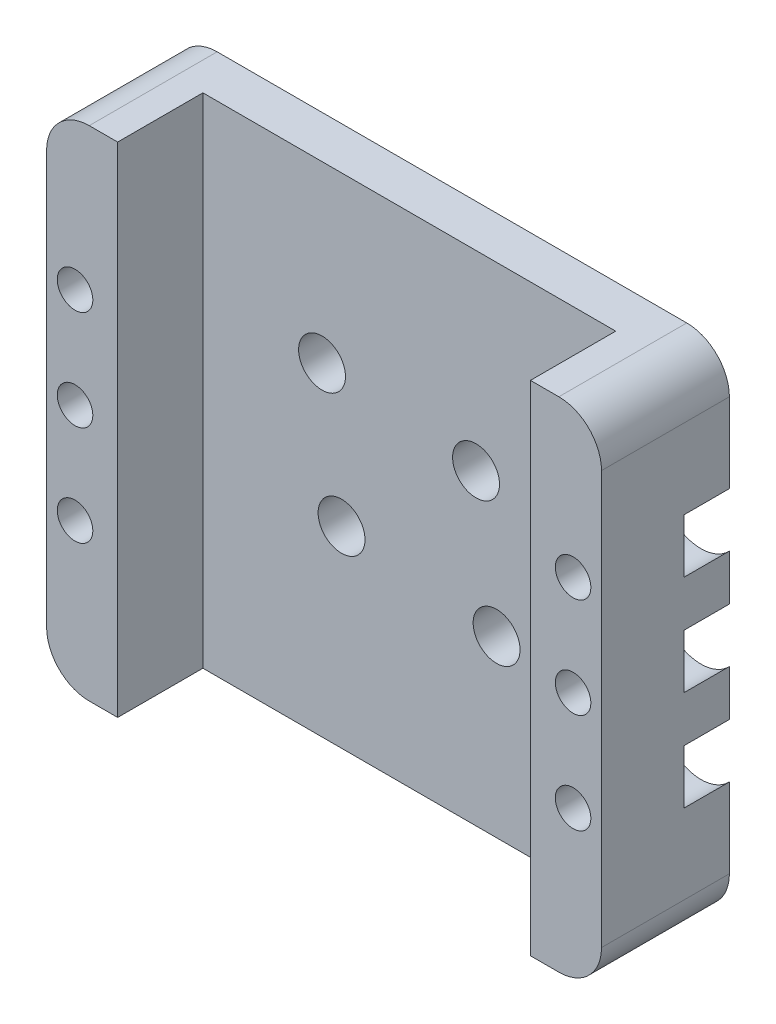
SolidWorks part; units mm, degrees
ref_plane "前视基准面" through (0, 0, 0) normal (0, 0, 1) x (1, 0, 0)
ref_plane "上视基准面" through (0, 0, 0) normal (0, 1, 0) x (1, 0, 0)
ref_plane "右视基准面" through (0, 0, 0) normal (1, 0, 0) x (0, 0, -1)
other "Configuration Table"
sketch "草图1" plane through (0, 0, 0) normal (0, 0, 1) x (-1, 0, 0)
  line L4 (-76.1943, 36.1142) -> (-76.1943, 1.0442)
  line L6 (-37.1443, 36.1142) -> (-37.1443, 1.0442)
  line L8 (-76.1943, 36.1142) -> (-37.1443, 36.1142)
  line L9 (-71.1943, 1.0442) -> (-71.1943, 36.1142)
  line L12 (-42.1443, 1.0442) -> (-42.1443, 36.1142)
  line L14 (-37.1443, 1.0442) -> (-76.1943, 1.0442)
  circle A6 centre (-62.8113, 23.8367) radius 1.65
  circle A9 centre (-50.5272, 13.3216) radius 1.65
  circle A11 centre (-74.1943, 25.6142) radius 1.25
  circle A12 centre (-74.1943, 11.5442) radius 1.25
  circle A13 centre (-74.1943, 18.5792) radius 1.25
  circle A14 centre (-39.1443, 25.6142) radius 1.25
  circle A15 centre (-39.1443, 18.5792) radius 1.25
  circle A16 centre (-39.1443, 11.5442) radius 1.25
  circle A17 centre (-51.9, 22.5808) radius 1.65
  circle A18 centre (-61.3649, 14.4695) radius 1.65
  point P3 (-74.1943, 36.1142)
  point P17 (-39.1443, 36.1142)
extrude "凸台-拉伸1" add sketch "草图1" along normal blind 3
sketch "草图2" plane through (0, 0, 0) normal (0, 0, -1) x (-1, 0, 0)
  line L0 (-76.1943, -1.0442) -> (-71.1943, -1.0442)
  line L1 (-37.1443, -1.0442) -> (-76.1943, -1.0442) construction
  line L2 (-71.1943, -1.0442) -> (-71.1943, -36.1142)
  line L3 (-76.1943, -36.1142) -> (-37.1443, -36.1142) construction
  line L4 (-71.1943, -36.1142) -> (-76.1943, -36.1142)
  line L5 (-76.1943, -36.1142) -> (-76.1943, -1.0442)
  line L6 (-37.1443, -1.0442) -> (-42.1443, -1.0442)
  line L7 (-42.1443, -1.0442) -> (-42.1443, -36.1142)
  line L8 (-42.1443, -36.1142) -> (-37.1443, -36.1142)
  line L9 (-37.1443, -36.1142) -> (-37.1443, -1.0442)
extrude "凸台-拉伸2" add sketch "草图2" along normal blind 1 and the other way blind 9
sketch "草图5" plane through (0, 0, 0) normal (0, 0, -1) x (-1, 0, 0)
  line L0 (-61.4385, -14.5775) -> (-51.9737, -22.6888) construction
  circle A0 centre (-56.7061, -18.6331) radius 1
sketch "草图6" plane through (42.1443, 0, 0) normal (1, 0, 0) x (0, 0, -1)
  line L0 (1, -1.0442) -> (0, -1.0442)
  line L1 (-9, -1.0442) -> (1, -1.0442) construction
  line L2 (0, -1.0442) -> (0, -36.1142)
  line L3 (0, -36.1142) -> (1, -36.1142)
  line L4 (1, -36.1142) -> (1, -1.0442)
extrude "切除-拉伸3" cut sketch "草图6" against normal blind 10 and the other way blind 41
sketch "草图7" plane through (0, 0, 0) normal (0, 0, -1) x (-1, 0, 0)
  circle A0 centre (-74.1943, -11.5442) radius 1.25
  circle A1 centre (-74.1943, -18.5792) radius 1.25
  circle A2 centre (-74.1943, -25.6142) radius 1.25
  circle A3 centre (-39.1443, -11.5442) radius 1.25
  circle A4 centre (-39.1443, -18.5792) radius 1.25
  circle A5 centre (-39.1443, -25.6142) radius 1.25
extrude "切除-拉伸4" cut sketch "草图7" against normal blind 27
sketch "草图10" plane through (0, 0, 9) normal (0, 0, 1) x (1, 0, 0)
  line L0 (42.1443, -1.0442) -> (41.1443, -1.0442)
  line L1 (37.1443, -1.0442) -> (42.1443, -1.0442) construction
  line L2 (41.1443, -1.0442) -> (41.1443, -36.1142)
  line L3 (42.1443, -36.1142) -> (37.1443, -36.1142) construction
  line L4 (41.1443, -36.1142) -> (42.1443, -36.1142)
  line L5 (42.1443, -36.1142) -> (42.1443, -1.0442)
  line L6 (71.1943, -1.0442) -> (72.1943, -1.0442)
  line L7 (71.1943, -1.0442) -> (76.1943, -1.0442) construction
  line L8 (72.1943, -1.0442) -> (72.1943, -36.1142)
  line L9 (76.1943, -36.1142) -> (71.1943, -36.1142) construction
  line L10 (72.1943, -36.1142) -> (71.1943, -36.1142)
  line L11 (71.1943, -36.1142) -> (71.1943, -1.0442)
fillet "圆角6" radius 3 1 edges at (37.1443, -36.1142, 4.5)
fillet "圆角7" radius 3 1 edges at (37.1443, -1.0442, 4.5)
fillet "圆角8" radius 3 2 edges at (76.1943, -36.1142, 4.5) (76.1943, -1.0442, 4.5)
sketch "草图12" plane through (0, 0, 9) normal (0, 0, 1) x (1, 0, 0)
  circle A0 centre (39.1443, -11.5442) radius 2.75
  circle A1 centre (39.1443, -18.5792) radius 2.75
  circle A2 centre (39.1443, -25.6142) radius 2.75
  circle A3 centre (74.1943, -11.5442) radius 2.75
  circle A4 centre (74.1943, -18.5792) radius 2.75
  circle A5 centre (74.1943, -25.6142) radius 2.75
sketch "草图13" plane through (0, 0, 0) normal (0, 0, -1) x (-1, 0, 0)
  circle A0 centre (-74.1943, -11.5442) radius 2.76
  circle A1 centre (-74.1943, -18.5792) radius 2.76
  circle A2 centre (-74.1943, -25.6142) radius 2.76
  circle A3 centre (-39.1443, -11.5442) radius 2.76
  circle A4 centre (-39.1443, -18.5792) radius 2.76
  circle A5 centre (-39.1443, -25.6142) radius 2.76
extrude "切除-拉伸7" cut sketch "草图13" against normal blind 3.2
